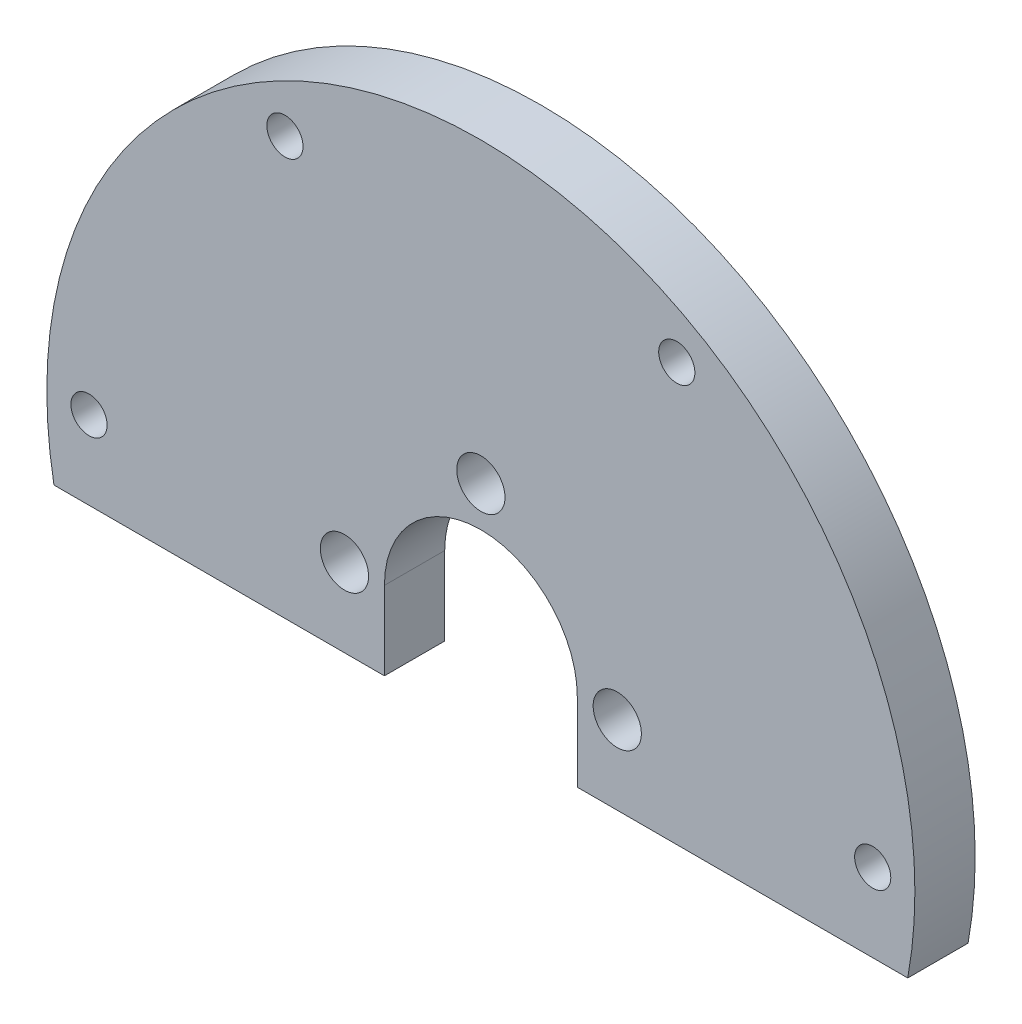
SolidWorks part; units mm, degrees
material "PLA Density Only"
ref_plane "Front Plane" through (0, 0, 0) normal (0, 0, 1) x (1, 0, 0)
ref_plane "Top Plane" through (0, 0, 0) normal (0, 1, 0) x (1, 0, 0)
ref_plane "Right Plane" through (0, 0, 0) normal (1, 0, 0) x (0, 0, -1)
sketch "Sketch1" plane through (0, 0, 0) normal (0, 0, 1) x (1, 0, 0)
  line L2 (-35.4083, -6.5) -> (35.4083, -6.5)
  line L3 (0, 0) -> (-32.5, 0) construction
  line L4 (0, 0) -> (0, 11.3137) construction
  line L5 (-7.9986, 0) -> (-7.9986, -6.5)
  line L6 (-7.9986, -6.5) -> (7.9986, -6.5)
  line L7 (7.9986, -6.5) -> (7.9986, 0)
  arc A1 (-35.4083, -6.5) -> (35.4083, -6.5) centre (0, 0) cw
  circle A2 centre (-32.5, 0) radius 1.5
  circle A3 centre (-16.25, 28.1458) radius 1.5
  circle A4 centre (16.25, 28.1458) radius 1.5
  circle A5 centre (32.5, 0) radius 1.5
  circle A6 centre (0, 11.3137) radius 2
  circle A7 centre (11.3137, 0) radius 2
  circle A8 centre (0, -11.3137) radius 2
  circle A9 centre (-11.3137, 0) radius 2
  arc A11 (-7.9986, 0) -> (7.9986, 0) centre (0, 0) cw
  point P1 (0, -6.5)
  dimension "D1" = 6.5
  dimension "D3" = 36
  dimension "D2" = 3
  dimension "D4" = 4
  dimension "D9" = 180
  dimension "D10" = 7.9986
  dimension "D6" = 32.5
  dimension "D7" = 4
  dimension "D8" = 16
  dimension "D5" = 4
extrude "Boss-Extrude1" add sketch "Sketch1" along normal blind 5 contours A1 L2 A9 A7 A6 A5 A4 A3 A2
